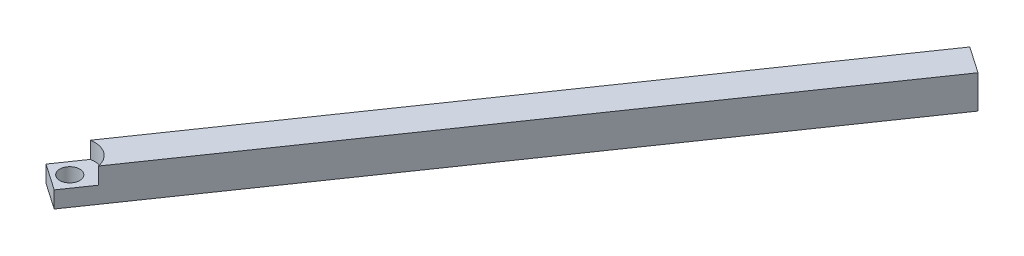
SolidWorks part; units mm, degrees
ref_plane "Front Plane" through (0, 0, 0) normal (0, 0, 1) x (1, 0, 0)
ref_plane "Top Plane" through (0, 0, 0) normal (0, 1, 0) x (1, 0, 0)
ref_plane "Right Plane" through (0, 0, 0) normal (1, 0, 0) x (0, 0, -1)
sketch "Sketch1" plane through (0, 0, 0) normal (0, 1, 0) x (1, 0, 0)
  line L0 (0, 0) -> (56.7733, 82.3213)
  line L1 (56.7733, 82.3213) -> (60.7542, 79.5759)
  line L2 (60.7542, 79.5759) -> (3.9809, -2.7454)
  line L3 (3.9809, -2.7454) -> (0, 0)
  line L4 (0, 0) -> (2.0991, 3.0437)
  line L20 (1.974, -1.3614) -> (6.1091, 4.6344) construction
  line L25 (3.3843, 4.9073) -> (7.3652, 2.1619) construction
  circle A1 centre (3.1827, 0.3912) radius 1.4997
  dimension "D1" = 1.4997
  dimension "D2" = 100
extrude "Boss-Extrude2" add sketch "Sketch1" along normal blind 5 contours L20 L3 L2 L1 A1 | L3 L20 A1 L1 L0
sketch "Sketch2" plane through (0, 5, 0) normal (0, 1, 0) x (1, 0, 0)
  line L1 (0, 0) -> (56.7733, 82.3213) construction
  line L2 (60.7542, 79.5759) -> (3.9809, -2.7454) construction
  line L3 (6.701, 1.1987) -> (3.9809, -2.7454)
  line L4 (3.9809, -2.7454) -> (0, 0)
  line L5 (0, 0) -> (2.7201, 3.9441)
  arc A0 (2.7201, 3.9441) -> (6.701, 1.1987) centre (3.3378, 0.581) cw
extrude "Cut-Extrude3" cut sketch "Sketch2" against normal blind 2.5
